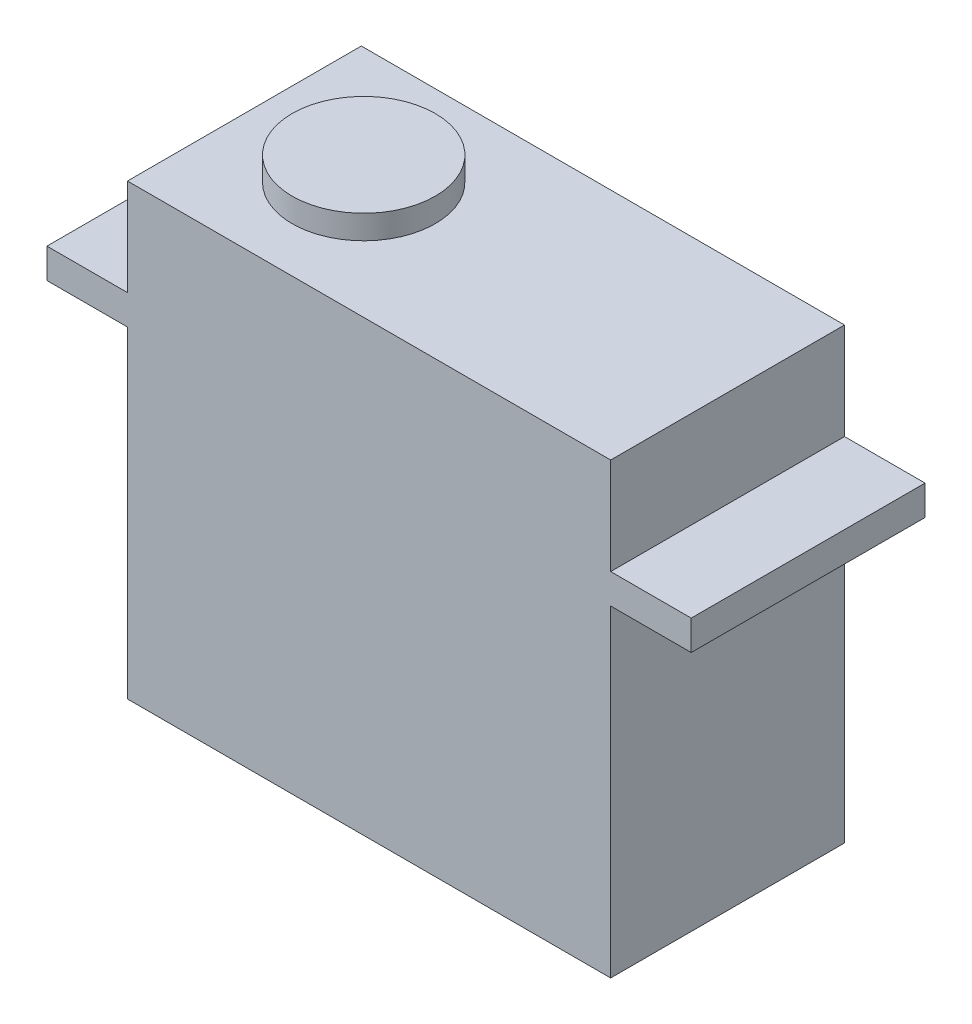
SolidWorks part; units mm, degrees
ref_plane "Front Plane" through (0, 0, 0) normal (0, 0, 1) x (1, 0, 0)
ref_plane "Top Plane" through (0, 0, 0) normal (0, 1, 0) x (1, 0, 0)
ref_plane "Right Plane" through (0, 0, 0) normal (1, 0, 0) x (0, 0, -1)
sketch "Sketch1" plane through (0, 0, 0) normal (0, 1, 0) x (1, 0, 0)
  line L1 (-20.25, -9.8) -> (20.25, -9.8)
  line L2 (-20.25, -9.8) -> (-20.25, 9.8)
  line L3 (-20.25, 9.8) -> (20.25, 9.8)
  line L4 (20.25, -9.8) -> (20.25, 9.8)
  line L5 (-20.25, -9.8) -> (20.25, 9.8) construction
  line L6 (-20.25, 9.8) -> (20.25, -9.8) construction
  point P0 (0, 0)
  dimension "D1" = 40.5
  dimension "D2" = 19.6
extrude "Boss-Extrude1" add sketch "Sketch1" along normal blind 37.6
sketch "Sketch2" plane through (0, 37.6, 0) normal (0, 1, 0) x (1, 0, 0)
  line L0 (-20.25, 0) -> (20.25, 0) construction
  line L1 (-20.25, 9.8) -> (-20.25, -9.8) construction
  line L2 (20.25, -9.8) -> (20.25, 9.8) construction
  line L3 (-10.25, 9.8) -> (-10.25, -9.8) construction
  line L4 (20.25, 9.8) -> (-20.25, 9.8) construction
  line L5 (-20.25, -9.8) -> (20.25, -9.8) construction
  circle A0 centre (-10.25, 0) radius 6
  dimension "D2" = 12
  dimension "D1" = 10
extrude "Boss-Extrude2" add sketch "Sketch2" along normal blind 2
sketch "Sketch3" plane through (0, 0, 9.8) normal (0, 0, 1) x (1, 0, 0)
  line L0 (-20.25, 29.5) -> (-27, 29.5)
  line L1 (-20.25, 37.6) -> (-20.25, 0) construction
  line L2 (-27, 29.5) -> (-27, 27)
  line L3 (-27, 27) -> (-20.25, 27)
  line L4 (-20.25, 27) -> (-20.25, 29.5)
  line L5 (20.25, 29.5) -> (27, 29.5)
  line L6 (20.25, 37.6) -> (20.25, 0) construction
  line L7 (27, 29.5) -> (27, 27)
  line L8 (27, 27) -> (20.25, 27)
  line L9 (20.25, 27) -> (20.25, 29.5)
  line L10 (-20.25, 0) -> (20.25, 0) construction
  dimension "D1" = 2.5
  dimension "D2" = 54
  dimension "D3" = 27
extrude "Boss-Extrude3" add sketch "Sketch3" against normal blind 19.6
